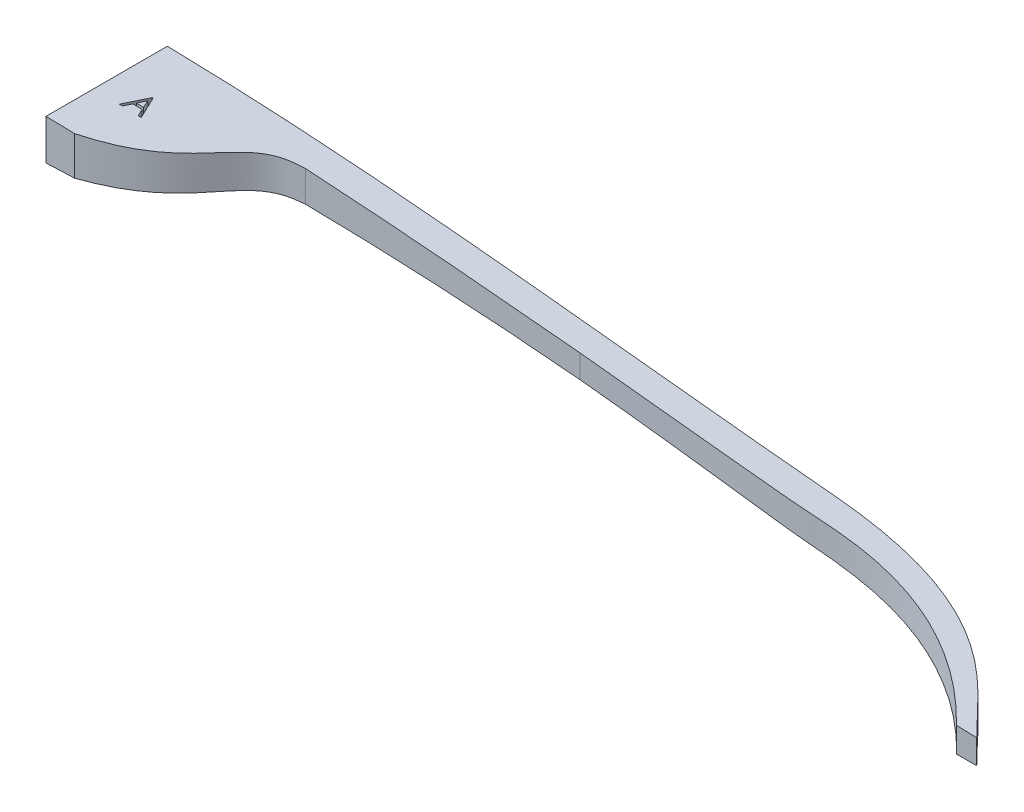
SolidWorks part; units mm, degrees
ref_plane "Front Plane" through (0, 0, 0) normal (0, 0, 1) x (1, 0, 0)
ref_plane "Top Plane" through (0, 0, 0) normal (0, 1, 0) x (1, 0, 0)
ref_plane "Right Plane" through (0, 0, 0) normal (1, 0, 0) x (0, 0, -1)
sketch "Sketch1" plane through (0, 0, 0) normal (0, 1, 0) x (1, 0, 0)
  line L1 (0, 0) -> (146.05, 0)
  line L2 (0, 0) -> (0, 19.05)
  line L3 (0, 19.05) -> (146.05, 19.05)
  line L4 (146.05, 0) -> (146.05, 19.05)
  dimension "D1" = 146.05
  dimension "D2" = 19.05
extrude "Boss-Extrude1" add sketch "Sketch1" along normal blind 15.24
sketch "Sketch3" plane through (0, 0, -19.05) normal (0, 0, -1) x (-1, 0, 0)
  line L0 (0, 15.24) -> (0, 0) construction
  line L1 (-146.05, 15.24) -> (-146.05, 0) construction
  spline S0 degree 3 poles (0, 8.89) (-26.7926, 10.0944) (-75.8961, 6.9149) (-124.0253, -0.8247) (-146.05, 0) knots 0 0 0 0 0.551608 1 1 1 1
  spline S1 degree 3 poles (0, 15.24) (-48.9151, 14.2813) (-97.1884, 5.218) (-146.05, 3.81) knots 0 0 0 0 1 1 1 1
  point P6 (-80.6679, 5.4839)
  point P11 (0, 0)
  point P13 (-80.6679, 8.89)
  line M1 (-146.05, 0) -> (0, 0)
  line M2 (0, 0) -> (0, 15.24)
  line M3 (0, 15.24) -> (-146.05, 15.24)
  line M4 (-146.05, 15.24) -> (-146.05, 0)
  dimension "D1" = 6.35
  dimension "D2" = 3.81
  dimension "D3" = 4.445
  dimension "D4" = 3.6908
sketch "Sketch6" plane through (0, 15.24, 0) normal (0, 1, 0) x (1, 0, 0)
  text T0 "<b>A</b>"
  point P1 (0, 0)
  point P2 (5.8031, 10.3046)
  point P3 (5.1741, 8.8558)
  point P4 (3.885, 7.5115)
  point P5 (0, 0)
  point P6 (0, 0)
extrude "Cut-Extrude5" cut sketch "Sketch6" against normal blind 1.905
sketch "Sketch4" plane through (0, 15.24, 0) normal (0, 1, 0) x (1, 0, 0)
  line L0 (146.05, 19.05) -> (0, 19.05) construction
  line L3 (4.4767, 0) -> (142.875, 0)
  line L4 (146.05, 0) -> (146.05, 19.05)
  line L5 (146.05, 19.05) -> (104.3032, 19.05)
  line L6 (0, 0) -> (146.05, 0) construction
  line L7 (146.05, 0) -> (146.05, 19.05) construction
  spline S0 degree 3 poles (4.4767, 0) (17.7258, 4.0431) (17.0053, 14.2049) (37.6932, 14.9861) (95.0665, 14.824) (108.0685, 14.714) (127.2268, 16.0497) (142.875, 0) knots 0 0 0 0 0.256127 0.322877 0.629203 0.700745 1 1 1 1
  spline S1 degree 3 poles (104.3032, 19.05) (131.3235, 19.1838) (139.2243, 6.6595) (146.05, 0) knots 0 0 0 0 1 1 1 1
  spline S2 degree 1 poles (26.2195, 14.4658) (68.9239, 14.8611) knots 0 0 1 1
  point P6 (0, 0)
  point P13 (0, 0)
  point P17 (0, 0)
  point P18 (0, 0)
  point P19 (26.0226, 11.7378)
  point P20 (94.5373, 16.2492)
  point P21 (0, 0)
  point P22 (99.2036, 15.3249)
  point P23 (0, 0)
  point P24 (100.1486, 14.2483)
  point P26 (0, 0)
  point P27 (26.4138, 13.3599)
  point P28 (0, 0)
  point P29 (101.7607, 15.5107)
  point P30 (0, 0)
  point P31 (68.9239, 14.7754)
  line M2 (146.05, 19.05) -> (0, 19.05)
  line M4 (0, 0) -> (146.05, 0)
  dimension "D1" = 3.175
extrude "Cut-Extrude2" cut sketch "Sketch4" against normal blind 19.05 contours S2 S0 M4 | S1 L4 M2
extrude "Cut-Extrude3" cut sketch "Sketch3" against normal through all contours S0 M2 M1 | S1 M3 M4
sketch "Sketch5" plane through (0, 0, 0) normal (-1, 0, 0) x (0, 0, 1)
  line L0 (0, 8.89) -> (-19.05, 8.89) construction
  line L1 (-5.715, 8.89) -> (-12.7, 8.89)
  line L2 (-5.715, 8.89) -> (-5.715, 12.7)
  line L3 (-5.715, 12.7) -> (-12.7, 12.7)
  line L4 (-12.7, 8.89) -> (-12.7, 12.7)
  line L5 (-19.05, 15.24) -> (-19.05, 8.89) construction
  dimension "D1" = 3.81
  dimension "D2" = 6.985
  dimension "D3" = 6.35
extrude "Cut-Extrude4" cut sketch "Sketch5" against normal blind 6.35
